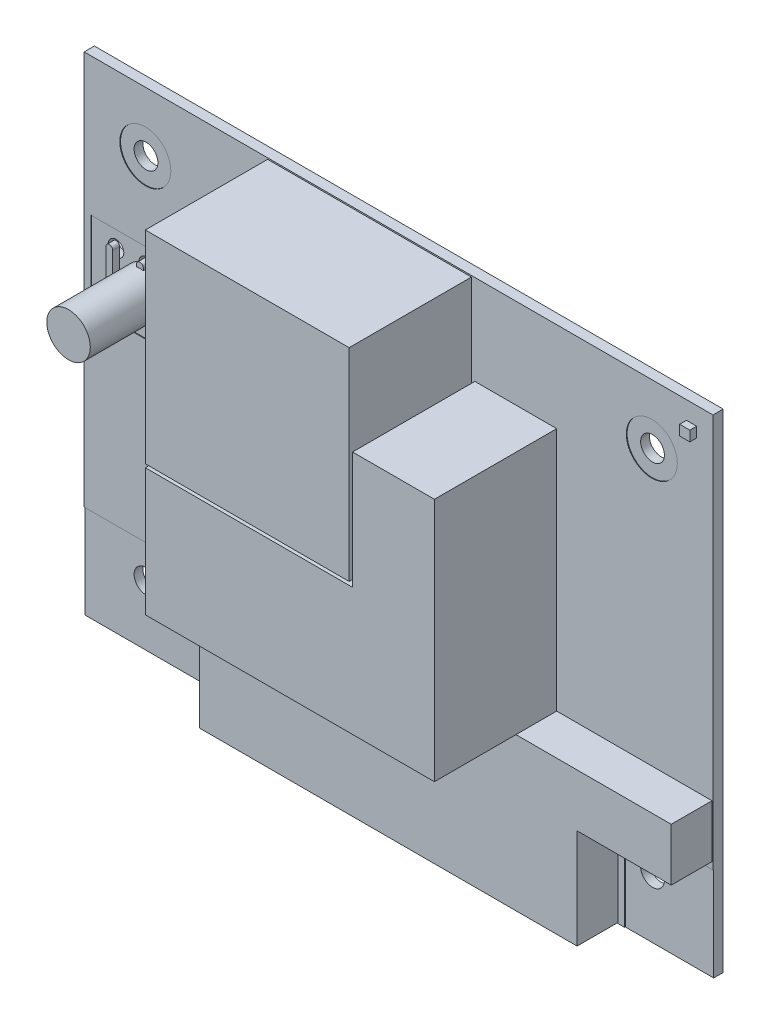
SolidWorks part; units mm, degrees
ref_plane "Face" through (0, 0, 0) normal (0, 0, 1) x (1, 0, 0)
ref_plane "Dessus" through (0, 0, 0) normal (0, 1, 0) x (1, 0, 0)
ref_plane "Droite" through (0, 0, 0) normal (1, 0, 0) x (0, 0, -1)
sketch "Esquisse1" plane through (0, 0, 0) normal (0, 0, 1) x (1, 0, 0)
  line L0 (-49.186, 0) -> (53.8427, 0) construction
  line L1 (-46.275, 33.6) -> (46.275, 33.6)
  line L3 (-46.275, -38.22) -> (46.275, -38.22)
  line L5 (0, -40.0182) -> (0, 45.548) construction
  line L7 (46.275, 33.6) -> (46.275, -38.22)
  line L9 (-46.275, 33.6) -> (-46.275, -38.22)
extrude "Base-Extrusion" add sketch "Esquisse1" against normal blind 1.5
sketch "Esquisse2" plane through (0, 0, 0) normal (0, 0, 1) x (1, 0, 0)
  line L0 (0, 34.9957) -> (0, -35.4731) construction
  line L1 (-43.8281, 0) -> (44.401, 0) construction
  line L4 (-37.275, 24.79) -> (41.1983, 24.79) construction
  line L5 (46.275, 33.6) -> (-46.275, 33.6) construction
  line L8 (-46.275, 33.6) -> (-46.275, -38.22) construction
  line L9 (46.275, -38.22) -> (46.275, 33.6) construction
  line L10 (37.275, 29.5068) -> (37.275, -33.6006) construction
  circle A0 centre (-37.275, 24.79) radius 1.75
  circle A1 centre (37.275, 24.79) radius 1.75
  circle A2 centre (-37.275, -29.41) radius 1.75
  circle A3 centre (37.275, -29.41) radius 1.75
  dimension "D4" = 3.5
  dimension "D5" = 9
  dimension "D6" = 9
  dimension "D1" = 8.81
  dimension "D2" = 74.55
  dimension "D3" = 54.2
  dimension "D7" = 74.55
  dimension "D8" = 9
  dimension "D9" = 9
extrude "Enlèv. mat.-Extru.1" cut sketch "Esquisse2" against normal through all
sketch "Esquisse11" plane through (0, 0, 0) normal (0, 0, 1) x (1, 0, 0)
  line L0 (-46.275, -24.41) -> (-46.275, -38.22)
  line L5 (-46.275, -24.41) -> (-24.275, -24.41)
  line L6 (-24.275, -24.41) -> (-24.275, -38.22)
  line L9 (-46.275, -38.22) -> (-24.275, -38.22)
  line L11 (33.275, -24.41) -> (46.275, -24.41)
  line L12 (33.275, -24.41) -> (33.275, -38.22)
  line L13 (46.275, -24.41) -> (46.275, -38.22)
  line L15 (46.275, -38.22) -> (33.275, -38.22)
extrude "Enlèv. mat.-Extru.2" cut sketch "Esquisse11" against normal blind 0.1
sketch "Esquisse12" plane through (0, 0, 0) normal (0, 0, 1) x (1, 0, 0)
  line L2 (32.275, -38.104) -> (32.275, -23.41)
  line L4 (-23.275, -38.104) -> (-23.275, -15.6493)
  line L5 (46.129, -15.6493) -> (-23.275, -15.6493)
  line L6 (-23.275, -38.104) -> (32.275, -38.104)
  line L7 (46.129, -15.6493) -> (46.129, -23.41)
  line L9 (46.275, -23.41) -> (33.275, -23.41)
  line L10 (46.129, -23.41) -> (32.275, -23.41)
  dimension "D1" = 1
extrude "Extrusion1" add sketch "Esquisse12" along normal blind 6
sketch "Esquisse13" plane through (0, 0, 0) normal (0, 0, 1) x (1, 0, 0)
  line L0 (-19.275, -15.6493) -> (23.275, -15.6493)
  line L2 (23.275, 20.3507) -> (11.225, 20.3507)
  line L3 (23.275, -15.6493) -> (23.275, 20.3507)
  line L4 (-19.275, 3.6) -> (10.725, 3.6)
  line L5 (10.725, 33.4) -> (10.725, 3.6)
  line L6 (-19.275, -15.6493) -> (-19.275, 3.1)
  line L7 (-19.275, 3.1) -> (11.225, 3.1)
  line L8 (11.225, 20.3507) -> (11.225, 3.1)
  line L9 (11.225, 33.6) -> (11.225, 3.1) construction
  line L10 (-19.275, 33.4) -> (10.725, 33.4)
  line L11 (-19.275, 3.6) -> (-19.275, 33.4)
  line L12 (10.725, 33.6) -> (10.725, 3.6) construction
  dimension "D2" = 30
  dimension "D3" = 0.5
extrude "Extrusion2" add sketch "Esquisse13" along normal blind 18
sketch "Esquisse14" plane through (0, 0, 0) normal (0, 0, 1) x (1, 0, 0)
  circle A0 centre (-37.275, 24.79) radius 3.75
  circle A1 centre (37.275, 24.79) radius 3.75
extrude "Enlèv. mat.-Extru.3" cut sketch "Esquisse14" against normal blind 0.1
sketch "Esquisse15" plane through (0, 0, -1.5) normal (0, 0, -1) x (-1, 0, 0)
  circle A0 centre (-37.275, 24.79) radius 3.75
  circle A1 centre (37.275, 24.79) radius 3.75
  circle A2 centre (37.275, -29.41) radius 3.75
  circle A3 centre (-37.275, -29.41) radius 3.75
extrude "Enlèv. mat.-Extru.4" cut sketch "Esquisse15" against normal blind 0.1
sketch "Esquisse16" plane through (0, 0, -1.5) normal (0, 0, -1) x (-1, 0, 0)
  line L0 (24.275, 16.1) -> (24.275, 0.6)
  line L1 (46.275, 33.6) -> (46.275, -38.22) construction
  line L2 (14.275, 16.1) -> (14.275, 0.6)
  line L3 (14.275, 16.1) -> (24.275, 16.1)
  line L4 (-46.275, 33.6) -> (46.275, 33.6) construction
  line L5 (14.275, 36.9149) -> (14.275, -43.6283) construction
  line L6 (24.275, 36.9149) -> (24.275, -43.6283) construction
  line L7 (14.275, 0.6) -> (24.275, 0.6)
  line L8 (3.275, 16.1) -> (13.275, 16.1)
  line L9 (13.275, 16.1) -> (13.275, 0.6)
  line L10 (3.275, 16.1) -> (3.275, 0.6)
  line L11 (3.275, 0.6) -> (13.275, 0.6)
  line L12 (-7.725, 16.1) -> (2.275, 16.1)
  line L13 (2.275, 16.1) -> (2.275, 0.6)
  line L14 (-7.725, 16.1) -> (-7.725, 0.6)
  line L15 (-7.725, 0.6) -> (2.275, 0.6)
  line L16 (-26.4257, -8.775) -> (36.0305, -8.775) construction
  line L17 (-7.725, -18.15) -> (2.275, -18.15)
  line L18 (-7.725, -33.65) -> (-7.725, -18.15)
  line L19 (2.275, -33.65) -> (2.275, -18.15)
  line L20 (-7.725, -33.65) -> (2.275, -33.65)
  line L21 (3.275, -18.15) -> (13.275, -18.15)
  line L22 (3.275, -33.65) -> (3.275, -18.15)
  line L23 (13.275, -33.65) -> (13.275, -18.15)
  line L24 (3.275, -33.65) -> (13.275, -33.65)
  line L25 (14.275, -18.15) -> (24.275, -18.15)
  line L26 (14.275, -33.65) -> (24.275, -33.65)
  line L27 (14.275, -33.65) -> (14.275, -18.15)
  line L28 (24.275, -33.65) -> (24.275, -18.15)
  dimension "D1" = 22
  dimension "D3" = 17.5
  dimension "D5" = 9.375
  dimension "D2" = 10
  dimension "D4" = 15.5
extrude "Extrusion3" add sketch "Esquisse16" along normal blind 4
sketch "Esquisse17" plane through (0, 0, -1.5) normal (0, 0, -1) x (-1, 0, 0)
  line L0 (21.075, -4.4) -> (22.475, -4.4)
  line L1 (21.075, 0.6) -> (21.075, -4.4)
  line L2 (18.575, 0.6) -> (18.575, -4.4)
  line L3 (19.975, 0.6) -> (19.975, -4.4)
  line L4 (18.575, 0.6) -> (19.975, 0.6)
  line L5 (18.575, -4.4) -> (19.975, -4.4)
  line L6 (-3.425, -4.4) -> (-2.025, -4.4)
  line L7 (21.075, 0.6) -> (22.475, 0.6)
  line L8 (-3.425, 0.6) -> (-3.425, -4.4)
  line L9 (-3.425, 0.6) -> (-2.025, 0.6)
  line L10 (-2.025, 0.6) -> (-2.025, -4.4)
  line L11 (7.575, 0.6) -> (8.975, 0.6)
  line L12 (8.975, 0.6) -> (8.975, -4.4)
  line L13 (22.475, 0.6) -> (22.475, -4.4)
  line L14 (7.575, 0.6) -> (7.575, -4.4)
  line L15 (7.575, -4.4) -> (8.975, -4.4)
  line L16 (16.075, 0.6) -> (16.075, -4.4)
  line L17 (16.075, 0.6) -> (17.475, 0.6)
  line L18 (17.475, 0.6) -> (17.475, -4.4)
  line L20 (16.075, -4.4) -> (17.475, -4.4)
  line L21 (10.075, 0.6) -> (10.075, -4.4)
  line L22 (10.075, -4.4) -> (11.475, -4.4)
  line L23 (11.475, 0.6) -> (11.475, -4.4)
  line L24 (10.075, 0.6) -> (11.475, 0.6)
  line L25 (5.075, 0.6) -> (6.475, 0.6)
  line L26 (6.475, 0.6) -> (6.475, -4.4)
  line L27 (5.075, -4.4) -> (6.475, -4.4)
  line L28 (5.075, 0.6) -> (5.075, -4.4)
  line L29 (0.475, 0.6) -> (0.475, -4.4)
  line L30 (-0.925, 0.6) -> (0.475, 0.6)
  line L31 (-0.925, 0.6) -> (-0.925, -4.4)
  line L32 (-0.925, -4.4) -> (0.475, -4.4)
  line L33 (-5.925, -4.4) -> (-4.525, -4.4)
  line L34 (-5.925, 0.6) -> (-4.525, 0.6)
  line L35 (-4.525, 0.6) -> (-4.525, -4.4)
  line L36 (-5.925, 0.6) -> (-5.925, -4.4)
  line L37 (-5.925, -18.15) -> (-5.925, -13.15)
  line L38 (-4.525, -18.15) -> (-4.525, -13.15)
  line L39 (-5.925, -18.15) -> (-4.525, -18.15)
  line L40 (-5.925, -13.15) -> (-4.525, -13.15)
  line L41 (-0.925, -13.15) -> (0.475, -13.15)
  line L42 (-0.925, -18.15) -> (-0.925, -13.15)
  line L43 (-0.925, -18.15) -> (0.475, -18.15)
  line L44 (0.475, -18.15) -> (0.475, -13.15)
  line L45 (5.075, -18.15) -> (5.075, -13.15)
  line L46 (5.075, -13.15) -> (6.475, -13.15)
  line L47 (6.475, -18.15) -> (6.475, -13.15)
  line L48 (5.075, -18.15) -> (6.475, -18.15)
  line L49 (10.075, -18.15) -> (11.475, -18.15)
  line L50 (11.475, -18.15) -> (11.475, -13.15)
  line L51 (10.075, -13.15) -> (11.475, -13.15)
  line L52 (10.075, -18.15) -> (10.075, -13.15)
  line L53 (16.075, -13.15) -> (17.475, -13.15)
  line L54 (17.475, -18.15) -> (17.475, -13.15)
  line L55 (16.075, -18.15) -> (17.475, -18.15)
  line L56 (16.075, -18.15) -> (16.075, -13.15)
  line L57 (7.575, -13.15) -> (8.975, -13.15)
  line L58 (7.575, -18.15) -> (7.575, -13.15)
  line L59 (22.475, -18.15) -> (22.475, -13.15)
  line L60 (8.975, -18.15) -> (8.975, -13.15)
  line L61 (7.575, -18.15) -> (8.975, -18.15)
  line L62 (-2.025, -18.15) -> (-2.025, -13.15)
  line L63 (-3.425, -18.15) -> (-2.025, -18.15)
  line L64 (-3.425, -18.15) -> (-3.425, -13.15)
  line L65 (21.075, -18.15) -> (22.475, -18.15)
  line L66 (-3.425, -13.15) -> (-2.025, -13.15)
  line L67 (18.575, -13.15) -> (19.975, -13.15)
  line L68 (18.575, -18.15) -> (19.975, -18.15)
  line L69 (19.975, -18.15) -> (19.975, -13.15)
  line L70 (18.575, -18.15) -> (18.575, -13.15)
  line L71 (21.075, -18.15) -> (21.075, -13.15)
  line L72 (21.075, -13.15) -> (22.475, -13.15)
extrude "Extrusion4" add sketch "Esquisse17" along normal blind 2
sketch "Esquisse18" plane through (7.725, 0, 0) normal (1, 0, 0) x (0, 0, -1)
  line L0 (1.5, -38.22) -> (1.5, 33.6) construction
  line L1 (1.5, 21.6635) -> (4.5, 21.6635)
  line L2 (1.5, 21.6635) -> (1.5, 9.6)
  line L3 (1.5, 9.6) -> (4.5, 9.6)
  line L4 (4.5, 21.6635) -> (4.5, 9.6)
  line L5 (5.5, 16.1) -> (5.5, 0.6) construction
  line L7 (5.5, 16.1) -> (1.5, 16.1) construction
  line L8 (4.5, -39.2135) -> (4.5, -27.15)
  line L12 (4.5, -8.775) -> (16.7081, -8.775) construction
  line L13 (1.5, -27.15) -> (4.5, -27.15)
  line L14 (1.5, -39.2135) -> (1.5, -27.15)
  line L15 (1.5, -39.2135) -> (4.5, -39.2135)
  dimension "D1" = 1
  dimension "D2" = 6.5
extrude "Enlèv. mat.-Extru.5" cut sketch "Esquisse18" against normal blind 40
sketch "Esquisse19" plane through (0, 0, -5.5) normal (0, 0, -1) x (-1, 0, 0)
  circle A0 centre (19.275, 13.2902) radius 1.75
  circle A1 centre (8.275, 13.2902) radius 1.75
  circle A2 centre (-2.725, 13.2902) radius 1.75
  circle A3 centre (-2.725, -30.8402) radius 1.75
  circle A4 centre (8.275, -30.8402) radius 1.75
  circle A5 centre (19.275, -30.8402) radius 1.75
extrude "Enlèv. mat.-Extru.6" cut sketch "Esquisse19" against normal blind 2
sketch "Esquisse20" plane through (0, 0, 0) normal (0, 0, 1) x (1, 0, 0)
  line L1 (42.3683, 30.9609) -> (43.8683, 30.9609)
  line L2 (42.3683, 30.9609) -> (42.3683, 29.4609)
  line L3 (42.3683, 29.4609) -> (43.8683, 29.4609)
  line L4 (43.8683, 30.9609) -> (43.8683, 29.4609)
  dimension "D1" = 1.5
  dimension "D2" = 1.5
extrude "Extrusion5" add sketch "Esquisse20" along normal blind 1
sketch "Esquisse21" plane through (0, 0, 0) normal (0, 0, 1) x (1, 0, 0)
  line L0 (46.275, 33.6) -> (-46.275, 33.6) construction
  line L1 (-45.275, 13.3) -> (-32.275, 13.3)
  line L2 (-45.275, 13.3) -> (-45.275, 1.5)
  line L3 (-45.275, 1.5) -> (-32.275, 1.5)
  line L4 (-32.275, 13.3) -> (-32.275, 1.5)
  line L5 (-46.275, 33.6) -> (-46.275, -24.41) construction
  dimension "D1" = 20.3
  dimension "D2" = 11.8
  dimension "D3" = 1
  dimension "D4" = 13
extrude "Enlèv. mat.-Extru.7" cut sketch "Esquisse21" against normal blind 0.1
sketch "Esquisse22" plane through (0, 0, -0.1) normal (0, 0, 1) x (1, 0, 0)
  line L0 (-45.275, 13.3) -> (-45.275, 1.5) construction
  line L1 (-32.275, 13.3) -> (-45.275, 13.3) construction
  circle A0 centre (-41.695, 10.8) radius 1.15
  circle A1 centre (-41.675, 4.8) radius 1.15
  circle A2 centre (-37.175, 10.8) radius 1.15
  circle A3 centre (-37.175, 4.8) radius 1.15
  dimension "D1" = 3.58
  dimension "D2" = 2.5
extrude "Enlèv. mat.-Extru.8" cut sketch "Esquisse22" against normal blind 10.1
sketch "Esquisse23" plane through (0, 0, -0.1) normal (0, 0, 1) x (1, 0, 0)
  circle A0 centre (-37.175, 7.8) radius 3.2
extrude "Extrusion6" add sketch "Esquisse23" along normal blind 11.5
sketch "Esquisse24" plane through (0, 0, -0.1) normal (0, 0, 1) x (1, 0, 0)
  line L0 (-37.675, 11.3) -> (-37.675, 4.3)
  line L1 (-42.175, 11.3) -> (-42.175, 4.3)
  line L2 (-41.175, 11.3) -> (-41.175, 4.3)
  line L3 (-36.675, 11.3) -> (-36.675, 4.3)
  arc A0 (-41.175, 11.3) -> (-42.175, 11.3) centre (-41.675, 11.3) ccw
  arc A1 (-42.175, 4.3) -> (-41.175, 4.3) centre (-41.675, 4.3) ccw
  arc A2 (-36.675, 11.3) -> (-37.675, 11.3) centre (-37.175, 11.3) ccw
  arc A3 (-37.675, 4.3) -> (-36.675, 4.3) centre (-37.175, 4.3) ccw
extrude "Extrusion7" add sketch "Esquisse24" along normal blind 1
